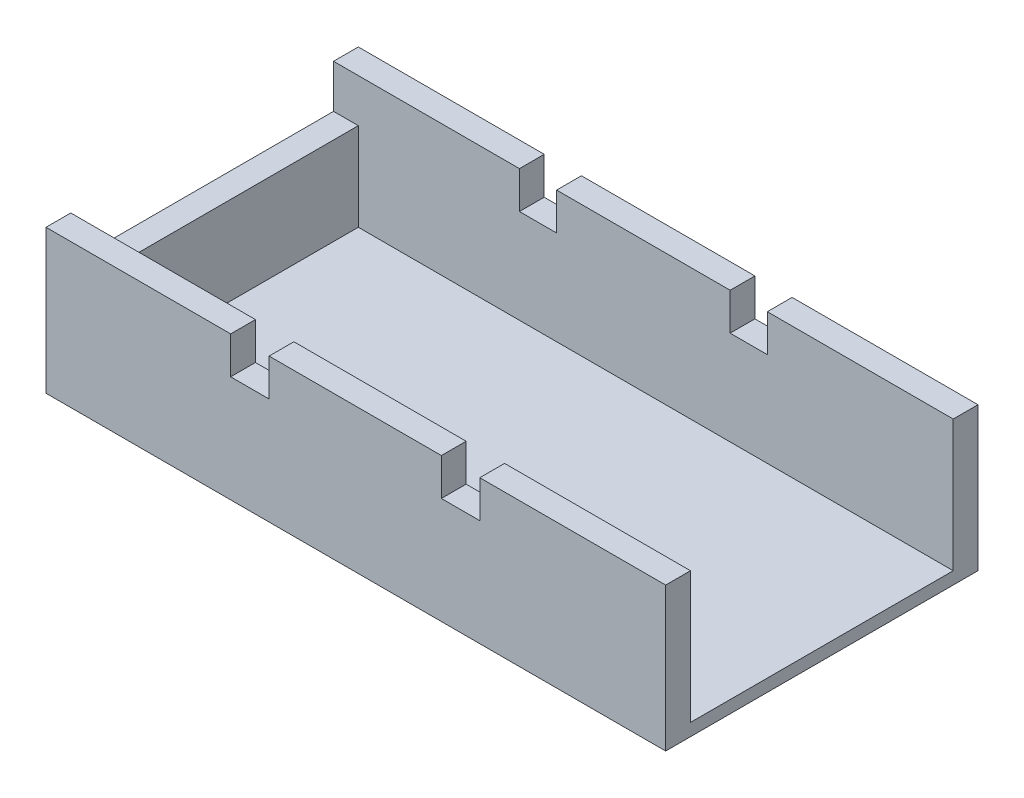
SolidWorks part; units mm, degrees
ref_plane "前视基准面" through (0, 0, 0) normal (0, 0, 1) x (1, 0, 0)
ref_plane "上视基准面" through (0, 0, 0) normal (0, 1, 0) x (1, 0, 0)
ref_plane "右视基准面" through (0, 0, 0) normal (1, 0, 0) x (0, 0, -1)
sketch "草图1" plane through (0, 0, 0) normal (0, 1, 0) x (1, 0, 0)
  line L1 (-25, -12.6) -> (25, -12.6)
  line L2 (-25, -12.6) -> (-25, 12.6)
  line L3 (-25, 12.6) -> (25, 12.6)
  line L4 (25, -12.6) -> (25, 12.6)
  line L5 (-25, -12.6) -> (25, 12.6) construction
  line L6 (-25, 12.6) -> (25, -12.6) construction
  point P0 (0, 0)
  dimension "D1" = 25.2
  dimension "D2" = 50
extrude "凸台-拉伸1" add sketch "草图1" along normal blind 1
sketch "草图2" plane through (0, 1, 0) normal (0, 1, 0) x (1, 0, 0)
  line L0 (-25, 12.6) -> (-25, 10.6)
  line L1 (-25, 12.6) -> (-25, -12.6) construction
  line L2 (-25, 10.6) -> (25, 10.6)
  line L3 (25, -12.6) -> (25, 12.6) construction
  line L4 (25, 10.6) -> (25, 12.6)
  line L5 (25, 12.6) -> (-25, 12.6)
  line L6 (-25, -10.6) -> (-25, -12.6)
  line L7 (-25, -12.6) -> (25, -12.6)
  line L8 (25, -12.6) -> (25, -10.6)
  line L9 (25, -10.6) -> (-25, -10.6)
  dimension "D1" = 2
  dimension "D2" = 2
extrude "凸台-拉伸2" add sketch "草图2" along normal blind 7.6
sketch "草图4" plane through (0, 8.6, 0) normal (0, 1, 0) x (1, 0, 0)
  line L0 (-25, 12.6) -> (-25, 10.6)
  line L1 (-25, 10.6) -> (-10, 10.6)
  line L2 (-25, 10.6) -> (25, 10.6) construction
  line L3 (-10, 10.6) -> (-10, 12.6)
  line L4 (25, 12.6) -> (-25, 12.6) construction
  line L5 (-10, 12.6) -> (-25, 12.6)
  line L6 (-7, 12.6) -> (-7, 10.6)
  line L7 (-7, 10.6) -> (7, 10.6)
  line L8 (7, 10.6) -> (7, 12.6)
  line L9 (7, 12.6) -> (-7, 12.6)
  line L10 (10, 12.6) -> (10, 10.6)
  line L11 (-25, 10.6) -> (25, 10.6) construction
  line L12 (10, 10.6) -> (25, 10.6)
  line L13 (25, 10.6) -> (25, 12.6)
  line L14 (25, 12.6) -> (10, 12.6)
  point P18 (-25, 11.6)
  dimension "D1" = 15
  dimension "D2" = 18
  dimension "D3" = 32
  dimension "D4" = 35
extrude "凸台-拉伸3" add sketch "草图4" along normal blind 3
sketch "草图5" plane through (0, 8.6, 0) normal (0, 1, 0) x (1, 0, 0)
  line L0 (-25, -10.6) -> (-10.1, -10.6)
  line L1 (25, -10.6) -> (-25, -10.6) construction
  line L2 (-10.1, -10.6) -> (-10.1, -12.6)
  line L3 (-25, -12.6) -> (25, -12.6) construction
  line L4 (-10.1, -12.6) -> (-25, -12.6)
  line L5 (-25, -10.6) -> (-25, -12.6)
  line L6 (-7, -12.6) -> (6.9, -12.6)
  line L7 (6.9, -12.6) -> (6.9, -10.6)
  line L8 (6.9, -10.6) -> (-7, -10.6)
  line L9 (-7, -10.6) -> (-7, -12.6)
  line L10 (10, -12.6) -> (25, -12.6)
  line L11 (25, -12.6) -> (25, -10.6)
  line L12 (25, -10.6) -> (10, -10.6)
  line L13 (10, -10.6) -> (10, -12.6)
  dimension "D1" = 14.9
  dimension "18.1" = 18
  dimension "D3" = 31.9
  dimension "D4" = 35
extrude "凸台-拉伸4" add sketch "草图5" along normal blind 3
sketch "草图6" plane through (0, 1, 0) normal (0, 1, 0) x (1, 0, 0)
  line L0 (-25, 12.6) -> (-23, 12.6)
  line L1 (-10, 12.6) -> (-25, 12.6) construction
  line L2 (-23, 12.6) -> (-23, -12.6)
  line L3 (-25, -12.6) -> (-10.1, -12.6) construction
  line L4 (-23, -12.6) -> (-25, -12.6)
  line L5 (-25, -12.6) -> (-25, 12.6)
  dimension "D2" = 2
extrude "凸台-拉伸5" add sketch "草图6" along normal blind 3.6
sketch "草图7" plane through (0, 4.6, 0) normal (0, 1, 0) x (1, 0, 0)
  line L4 (-23, -10.6) -> (-23, 10.6)
  line L5 (-23, 10.6) -> (-25, 10.6)
  line L6 (-25, 10.6) -> (-25, -10.6)
  line L7 (-25, -10.6) -> (-23, -10.6)
  line L8 (-23, -10.6) -> (-23, 10.6)
  line L9 (-23, 10.6) -> (-25, 10.6)
  line L10 (-25, 10.6) -> (-25, -10.6)
  line L11 (-25, -10.6) -> (-23, -10.6)
  dimension "D1" = 0
extrude "凸台-拉伸6" add sketch "草图7" along normal blind 3.5
